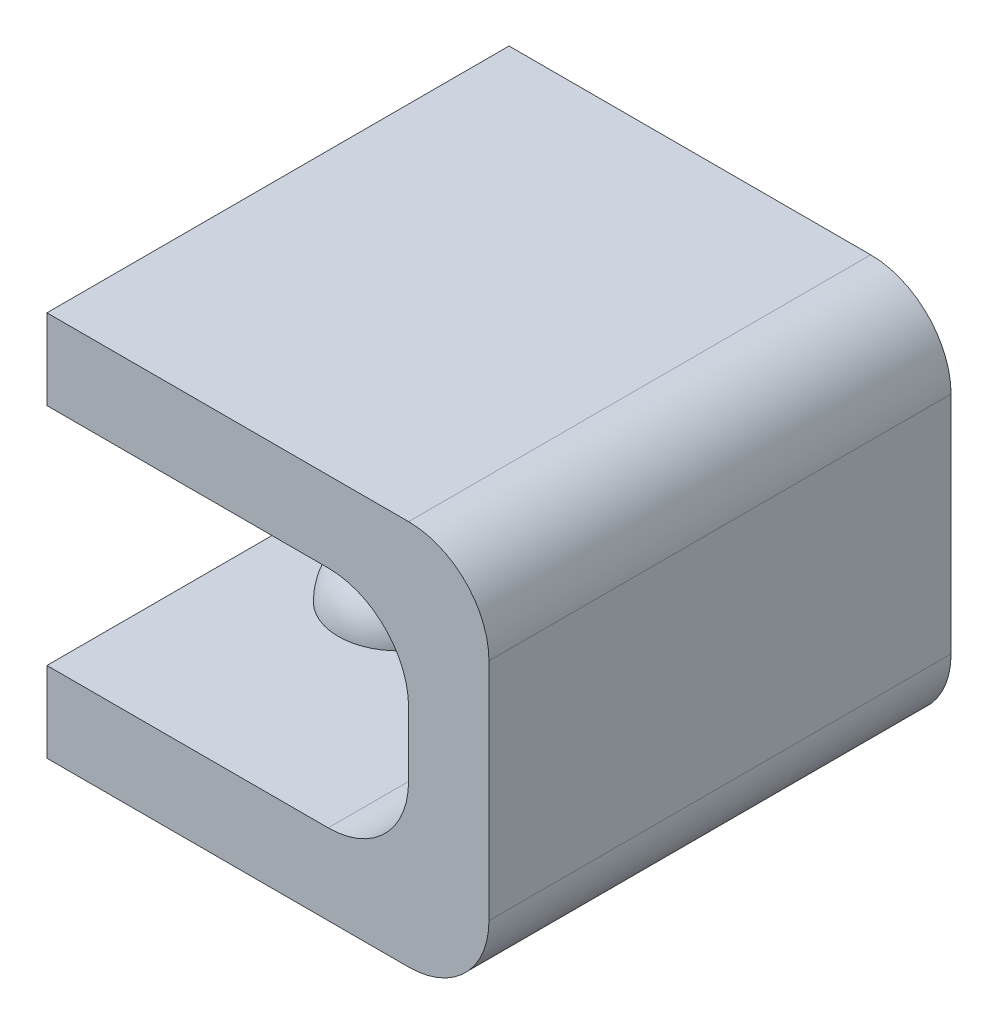
SolidWorks part; units mm, degrees
ref_plane "Front Plane" through (0, 0, 0) normal (0, 0, 1) x (1, 0, 0)
ref_plane "Top Plane" through (0, 0, 0) normal (0, 1, 0) x (1, 0, 0)
ref_plane "Right Plane" through (0, 0, 0) normal (1, 0, 0) x (0, 0, -1)
sketch "Sketch1" plane through (0, 0, 0) normal (0, 0, 1) x (1, 0, 0)
  line L0 (-9, 2.8) -> (0, 2.8)
  line L1 (0, 2.8) -> (0, -2.8)
  line L2 (0, -2.8) -> (-9, -2.8)
  line L3 (-9, -2.8) -> (-9, -4.8)
  line L4 (-9, -4.8) -> (2, -4.8)
  line L5 (2, -4.8) -> (2, 4.8)
  line L6 (2, 4.8) -> (-9, 4.8)
  line L7 (-9, 4.8) -> (-9, 2.8)
  point P2 (0, 0)
  dimension "D1" = 5.6
  dimension "D2" = 2
  dimension "D3" = 2
  dimension "D4" = 2
  dimension "D5" = 9
extrude "Boss-Extrude1" add sketch "Sketch1" along normal blind 11.5
sketch "Sketch2" plane through (0, 2.8, 0) normal (0, -1, 0) x (1, 0, 0)
  line L0 (-6, 4.25) -> (-6, 7.25)
  line L1 (-9, 11.5) -> (-9, 0) construction
  arc A0 (-6, 4.25) -> (-6, 7.25) centre (-6, 5.75) cw
  point P3 (0, 0)
  point P4 (0, 0)
  point P5 (0, 0)
  point P8 (-9, 5.75)
  dimension "D1" = 3
  dimension "D2" = 3
revolve "Revolve1" add sketch "Sketch2" angle 180 about L0
mirror "Mirror1" about plane through (0, 0, 0) normal (0, 1, 0) of "Revolve1"
fillet "Fillet1" radius 2 4 edges at (2, -4.8, 5.75) (2, 4.8, 5.75) (0, 2.8, 5.75) (0, -2.8, 5.75)
